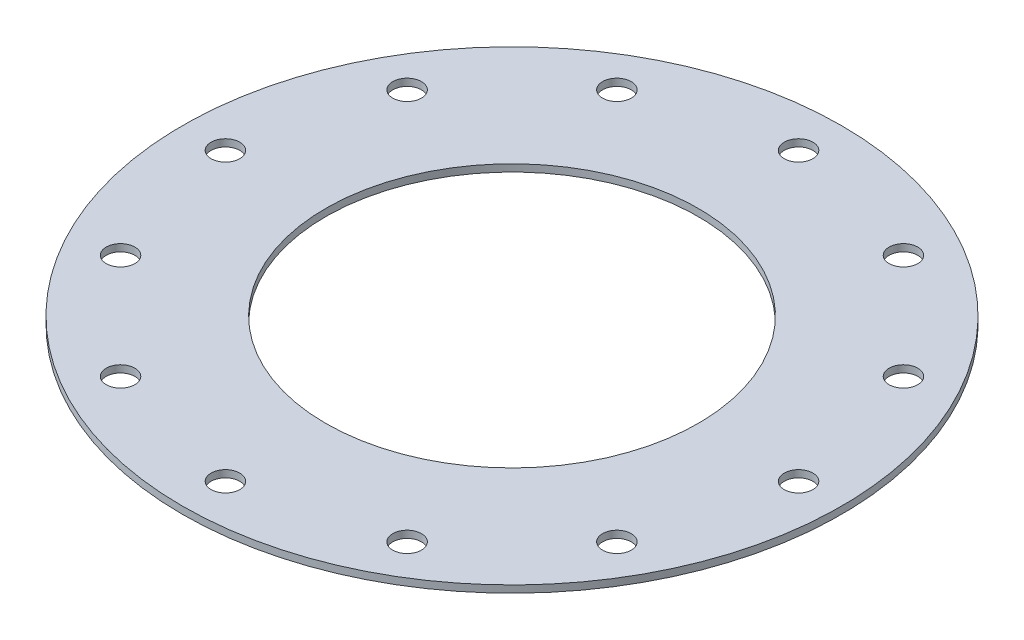
SolidWorks part; units mm, degrees
material "Natural Rubber"
ref_plane "Front Plane" through (0, 0, 0) normal (0, 0, 1) x (1, 0, 0)
ref_plane "Top Plane" through (0, 0, 0) normal (0, 1, 0) x (1, 0, 0)
ref_plane "Right Plane" through (0, 0, 0) normal (1, 0, 0) x (0, 0, -1)
sketch "Sketch2" plane through (0, 0, 0) normal (0, 1, 0) x (1, 0, 0)
  circle A0 centre (0, 0) radius 115
  circle A1 centre (0, 100) radius 5
  circle A2 centre (50, 86.6025) radius 5
  circle A3 centre (86.6025, 50) radius 5
  circle A4 centre (100, 0) radius 5
  circle A5 centre (86.6025, -50) radius 5
  circle A6 centre (50, -86.6025) radius 5
  circle A7 centre (0, -100) radius 5
  circle A8 centre (-50, -86.6025) radius 5
  circle A9 centre (-86.6025, -50) radius 5
  circle A10 centre (-100, 0) radius 5
  circle A11 centre (-86.6025, 50) radius 5
  circle A12 centre (-50, 86.6025) radius 5
  circle A13 centre (0, 0) radius 65
  point P29 (0, 0)
  dimension "D1" = 230
  dimension "D2" = 10
  dimension "D5" = 130
  dimension "D3" = 100
  dimension "D4" = 12
extrude "Boss-Extrude1" add sketch "Sketch2" along normal blind 2.5
equation "\"d\" = 13cm"
equation "\"D1@Sketch2\"=\"d\"+5*\"thiq\""
equation "\"thiq\"= 2cm"
equation "\"screw\"= 1cm"
equation "\"D2@Sketch2\"=\"screw\""
equation "\"D3@Sketch2\"=(\"d\"+(3.5*\"thiq\"))/2"
equation "\"D5@Sketch2\"=\"d\""
